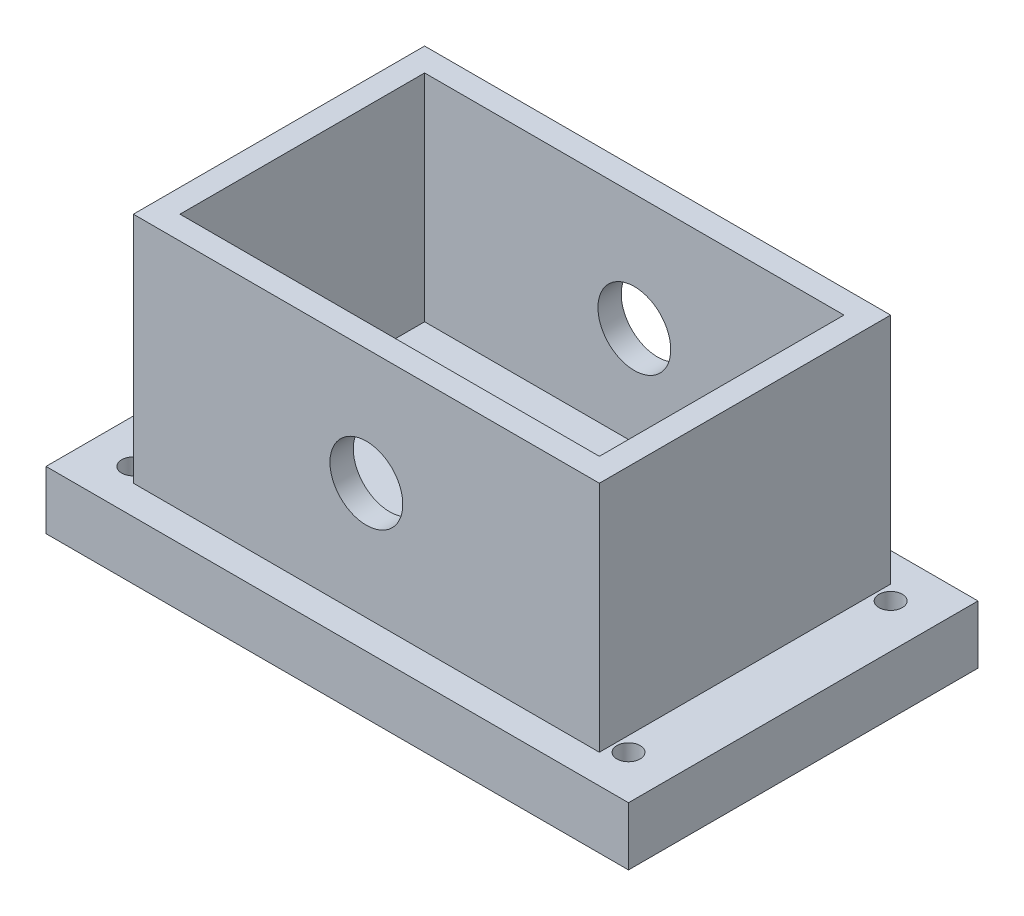
SolidWorks part; units mm, degrees
ref_plane "前视基准面" through (0, 0, 0) normal (0, 0, 1) x (1, 0, 0)
ref_plane "上视基准面" through (0, 0, 0) normal (0, 1, 0) x (1, 0, 0)
ref_plane "右视基准面" through (0, 0, 0) normal (1, 0, 0) x (0, 0, -1)
sketch "草图1" plane through (0, 0, 0) normal (0, 1, 0) x (1, 0, 0)
  line L0 (-100, 60) -> (100, 60)
  line L1 (100, 60) -> (100, -60)
  line L2 (100, -60) -> (-100, -60)
  line L3 (-100, -60) -> (-100, 60)
extrude "凸台-拉伸1" add sketch "草图1" along normal blind 20
ref_plane "基准面1" through (0, 20, 0) normal (0, 1, 0) x (1, 0, 0)
sketch "草图2" plane through (0, 20, 0) normal (0, 1, 0) x (1, 0, 0)
  line L0 (-80, 50) -> (80, 50)
  line L1 (80, 50) -> (80, -50)
  line L2 (80, -50) -> (-80, -50)
  line L3 (-80, -50) -> (-80, 50)
extrude "凸台-拉伸2" add sketch "草图2" along normal blind 80
ref_plane "基准面2" through (0, 26, 0) normal (0, 1, 0) x (1, 0, 0)
sketch "草图3" plane through (0, 26, 0) normal (0, 1, 0) x (1, 0, 0)
  line L0 (-72, 42) -> (72, 42)
  line L1 (72, 42) -> (72, -42)
  line L2 (72, -42) -> (-72, -42)
  line L3 (-72, -42) -> (-72, 42)
extrude "切除-拉伸1" cut sketch "草图3" along normal through all
sketch "草图4" plane through (0, 0, 0) normal (0, 1, 0) x (1, 0, 0)
  circle A0 centre (85, -45) radius 4
  circle A1 centre (85, 45) radius 4
  circle A2 centre (-85, -45) radius 4
  circle A3 centre (-85, 45) radius 4
extrude "切除-拉伸2" cut sketch "草图4" along normal through all
sketch "草图5" plane through (0, 0, 0) normal (0, 0, 1) x (1, 0, 0)
  circle A0 centre (0, 60) radius 12.5
extrude "切除-拉伸3" cut sketch "草图5" against normal mid plane 402
